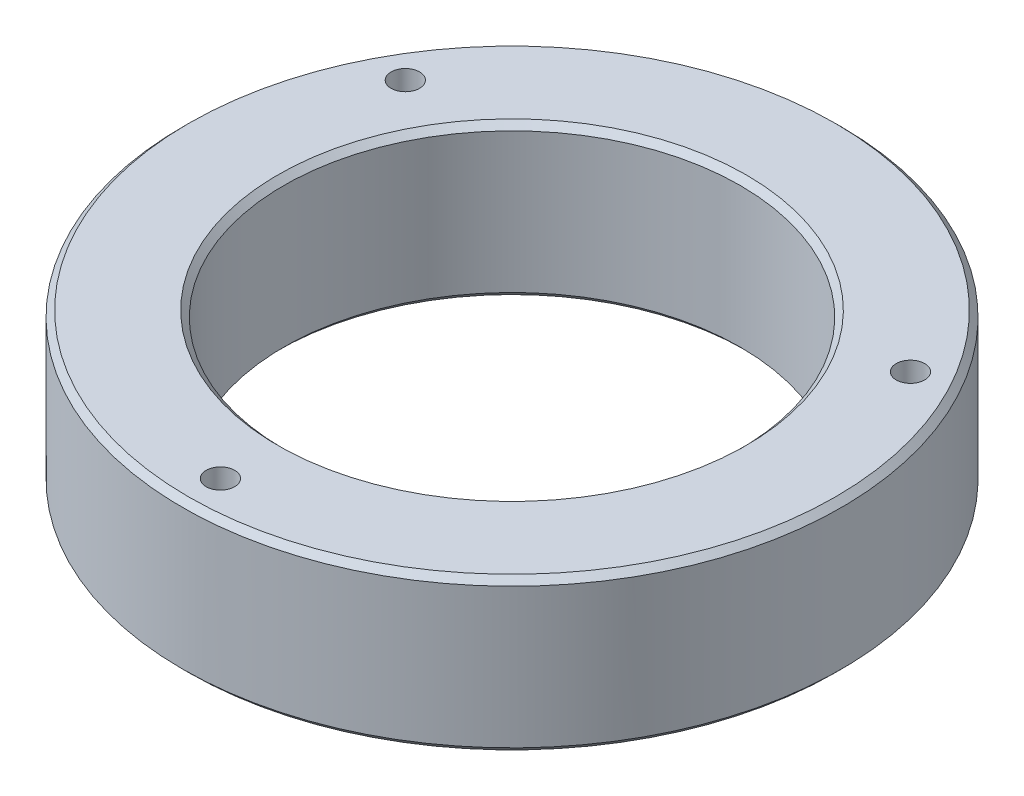
SolidWorks part; units mm, degrees
ref_plane "Front Plane" through (0, 0, 0) normal (1, 0, 0) x (0, 1, 0)
ref_plane "Top Plane" through (0, 0, 0) normal (0, 0, 1) x (0, 1, 0)
ref_plane "Right Plane" through (0, 0, 0) normal (0, 1, 0) x (-1, 0, 0)
sketch "Sketch1" plane through (0, 0, 0) normal (0, 0, 1) x (0, 1, 0)
  line L0 (-19.05, 82.5246) -> (19.05, 82.5246)
  line L1 (19.05, 82.5246) -> (19.05, 57.15)
  line L2 (19.05, 57.15) -> (-19.05, 57.15)
  line L3 (-19.05, 57.15) -> (-19.05, 82.5246)
  line L4 (-44.45, 0) -> (44.45, 0) construction
  dimension "D1" = 38.1
  dimension "D2" = 25.3746
  dimension "D3" = 82.5246
revolve "Revolve1" add sketch "Sketch1" angle 360 about L4
hole_wizard "CBORE for 1/4 Socket Head Cap Screw1" positions "Sketch3" profile "Sketch2" counterbore size "1/4" standard "ANSI Inch"
sketch "Sketch3" plane through (0, -19.05, 0) normal (0, -1, 0) x (-1, 0, 0)
  circle A0 centre (0, 0.0068) radius 73.0318 construction
  circle A1 centre (0, 0) radius 57.15 construction
  point P0 (0, -73.025)
  point P1 (-63.246, 36.5252)
  point P3 (63.246, 36.5252)
  dimension "D1" = 146.0637
  dimension "D2" = 63.246
  dimension "D3" = 63.246
  dimension "D4" = 0.0068
  dimension "D5" = 36.5252
  dimension "D6" = 73.025
sketch "Sketch2" plane through (0, -19.05, 73.025) normal (1, 0, 0) x (0, 0, -1)
  line L0 (0, 0) -> (0, 40.2443)
  line L1 (0, 40.2443) -> (3.5687, 38.1)
  line L2 (3.5687, 38.1) -> (3.5687, 9.652)
  line L3 (3.5687, 9.652) -> (5.5626, 9.652)
  line L4 (5.5626, 9.652) -> (5.5626, 0)
  line L5 (5.5626, 0) -> (0, 0)
  line L10 (0, 40.2443) -> (-3.5687, 38.1) construction
  line L11 (0, -6.35) -> (0, 107.95) construction
  dimension "Hole Dia." = 7.1374
  dimension "Hole Depth" = 38.1
  dimension "C'Bore Dia." = 11.1252
  dimension "C'Bore Depth" = 9.652
  dimension "Drill Angle" = 118
hole_wizard "3/8-16 Tapped Hole2" positions "Sketch7" profile "Sketch6" tap size "3/8-16" standard "ANSI Inch"
sketch "Sketch7" plane through (0, -19.05, 0) normal (0, -1, 0) x (-1, 0, 0)
  circle A0 centre (0, -73.025) radius 5.5626 construction
  point P0 (-69.85, 0)
  point P1 (69.85, 0)
  dimension "D1" = 69.85
  dimension "D2" = 69.85
  dimension "D3" = 73.025
  dimension "D4" = 73.025
sketch "Sketch6" plane through (69.85, -19.05, 0) normal (1, 0, 0) x (0, 0, -1)
  line L0 (0, 0) -> (0, 27.7847)
  line L1 (0, 27.7847) -> (3.9687, 25.4)
  line L2 (3.9687, 25.4) -> (3.9687, 0)
  line L5 (3.9687, 0) -> (0, 0)
  line L10 (0, 27.7847) -> (-3.9687, 25.4) construction
  line L11 (0, -6.35) -> (0, 107.95) construction
  dimension "Tap Drill Dia." = 7.9375
  dimension "Tap Drill Depth" = 25.4
  dimension "Drill Angle" = 118
cosmetic thread "Hole Thread3" parameters "D1"=19.05, "D2"=9.525
cosmetic thread "Hole Thread4" parameters "D1"=19.05, "D2"=9.525
chamfer "Chamfer1" distance 1.524 angle 45 4 edges at (0, 19.05, -57.15) (0, -19.05, -57.15) (0, 19.05, -82.5246) (0, -19.05, -82.5246)
